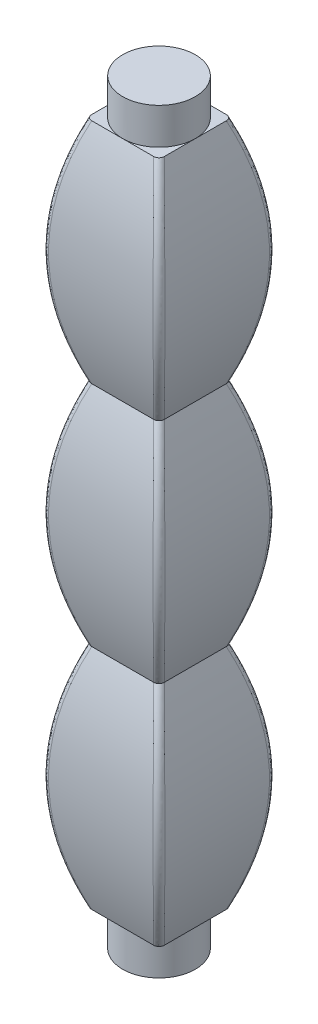
SolidWorks part; units mm, degrees
ref_plane "Front Plane" through (0, 0, 0) normal (0, 0, 1) x (1, 0, 0)
ref_plane "Top Plane" through (0, 0, 0) normal (0, 1, 0) x (1, 0, 0)
ref_plane "Right Plane" through (0, 0, 0) normal (1, 0, 0) x (0, 0, -1)
sketch "Sketch1" plane through (0, 0, 0) normal (0, 0, 1) x (1, 0, 0)
  line L0 (0, 3.2665) -> (2.5, 3.2665)
  line L1 (0, -5.1135) -> (0, 29.2665) construction
  line L5 (2.5, 3.2665) -> (2.5, 5.7665)
  line L14 (-37.8853, 29.2665) -> (41.7137, 29.2665) construction
  line L16 (2.5, 52.7665) -> (2.5, 55.2665) construction
  line L17 (0, 3.2665) -> (0, 29.2665)
  line L18 (0, 63.6465) -> (0, 55.2665) construction
  line L19 (2.5, 5.7665) -> (2.5, 3.2665) construction
  line L20 (2.5, 55.2665) -> (2.5, 52.7665)
  line L21 (0, 55.2665) -> (2.5, 55.2665)
  line L22 (0, 29.2665) -> (0, 5.9372) construction
  line L23 (0, 55.2665) -> (0, 29.2665)
  line L25 (2.5, 52.7665) -> (0.8575, 52.7665)
  line L27 (2.5, 5.7665) -> (0.8575, 5.7665)
  line L28 (0.8575, 52.7665) -> (0.8575, 5.7665)
  point P3 (0, 3.1872)
  point P18 (0, 55.3457)
  point P26 (2.7717, 38.2468)
  dimension "D1" = 2.5
  dimension "D2" = 2.5
  dimension "D3" = 52
  dimension "D4" = 2.5
revolve "Revolve1" add sketch "Sketch1" angle 360 about L17
ref_plane "Plane1" through (0, 52.7665, 0) normal (0, -1, 0) x (-1, 0, 0)
ref_plane "Plane2" through (0, 5.7665, 0) normal (0, 1, 0) x (1, 0, 0)
sketch "Sketch2" plane through (0, 52.7665, 0) normal (0, -1, 0) x (-1, 0, 0)
  line L1 (-2.5, -2.5) -> (2.5, -2.5)
  line L2 (-2.5, -2.5) -> (-2.5, 2.5)
  line L3 (-2.5, 2.5) -> (2.5, 2.5)
  line L4 (2.5, -2.5) -> (2.5, 2.5)
  line L5 (-2.5, -2.5) -> (2.5, 2.5) construction
  line L6 (-2.5, 2.5) -> (2.5, -2.5) construction
  point P0 (0, 0)
  dimension "D2" = 5
sketch "Sketch3" plane through (0, 5.7665, 0) normal (0, 1, 0) x (1, 0, 0)
  line L1 (-2.5, -2.5) -> (2.5, -2.5)
  line L2 (-2.5, -2.5) -> (-2.5, 2.5)
  line L3 (-2.5, 2.5) -> (2.5, 2.5)
  line L4 (2.5, -2.5) -> (2.5, 2.5)
  line L5 (-2.5, -2.5) -> (2.5, 2.5) construction
  line L6 (-2.5, 2.5) -> (2.5, -2.5) construction
  point P0 (0, 0)
  dimension "D1" = 5
ref_plane "Plane3" through (0, 21.4331, 0) normal (0, 1, 0) x (1, 0, 0)
ref_plane "Plane4" through (0, 37.0998, 0) normal (0, -1, 0) x (-1, 0, 0)
sketch "Sketch4" plane through (0, 21.4331, 0) normal (0, 1, 0) x (1, 0, 0)
  line L1 (-2.5, -2.5) -> (2.5, -2.5)
  line L2 (-2.5, -2.5) -> (-2.5, 2.5)
  line L3 (-2.5, 2.5) -> (2.5, 2.5)
  line L4 (2.5, -2.5) -> (2.5, 2.5)
  line L5 (-2.5, -2.5) -> (2.5, 2.5) construction
  line L6 (-2.5, 2.5) -> (2.5, -2.5) construction
sketch "Sketch5" plane through (0, 37.0998, 0) normal (0, -1, 0) x (-1, 0, 0)
  line L1 (-2.5, -2.5) -> (2.5, -2.5)
  line L2 (-2.5, -2.5) -> (-2.5, 2.5)
  line L3 (-2.5, 2.5) -> (2.5, 2.5)
  line L4 (2.5, -2.5) -> (2.5, 2.5)
  line L5 (-2.5, -2.5) -> (2.5, 2.5) construction
  line L6 (-2.5, 2.5) -> (2.5, -2.5) construction
  point P0 (0, 0)
ref_plane "Plane5" through (0, 44.9331, 0) normal (0, -1, 0) x (-1, 0, 0)
sketch "Sketch6" plane through (0, 44.9331, 0) normal (0, -1, 0) x (-1, 0, 0)
  line L1 (-4, -4) -> (4, -4)
  line L2 (-4, -4) -> (-4, 4)
  line L3 (-4, 4) -> (4, 4)
  line L4 (4, -4) -> (4, 4)
  line L5 (-4, -4) -> (4, 4) construction
  line L6 (-4, 4) -> (4, -4) construction
  point P0 (0, 0)
  dimension "D1" = 8
loft "Loft1" add profiles "Sketch2", "Sketch6", "Sketch5"
pattern_linear "LPattern1" count 3 spacing 15.666 along (0, -1, 0) of "Loft1"
fillet "Fillet5" radius 0.4 12 edges
